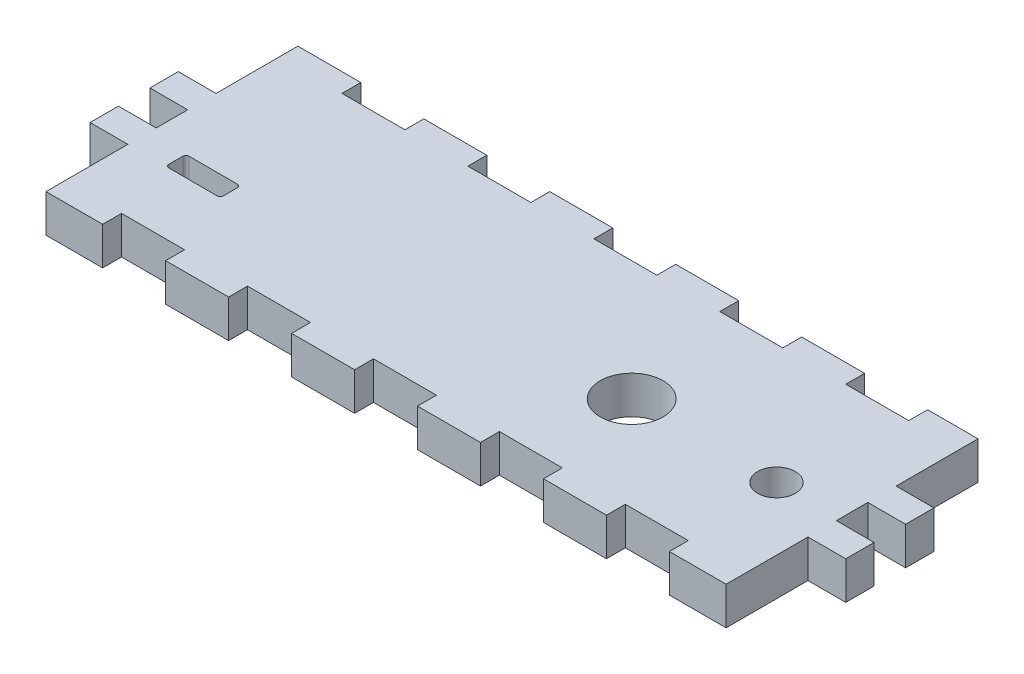
SolidWorks part; units mm, degrees
ref_plane "Спереди" through (0, 0, 0) normal (0, 0, 1) x (1, 0, 0)
ref_plane "Сверху" through (0, 0, 0) normal (0, 1, 0) x (1, 0, 0)
ref_plane "Справа" through (0, 0, 0) normal (1, 0, 0) x (0, 0, -1)
sketch "Эскиз1" plane through (0, 0, 0) normal (0, 1, 0) x (1, 0, 0)
  line L1 (0, 0) -> (112, 0)
  line L2 (0, 0) -> (0, -40)
  line L3 (0, -40) -> (112, -40)
  line L4 (112, 0) -> (112, -40)
  dimension "D1" = 40
  dimension "D2" = 112
extrude "Бобышка-Вытянуть1" add sketch "Эскиз1" along normal blind 6
sketch "Эскиз2" plane through (0, 6, 0) normal (0, 1, 0) x (1, 0, 0)
  line L1 (112, 0) -> (0, 0) construction
  line L2 (112, -40) -> (112, 0) construction
  circle A0 centre (102, -25) radius 3
  dimension "D1" = 6
  dimension "D2" = 22
  dimension "D3" = 10
extrude "Вырез-Вытянуть1" cut sketch "Эскиз2" against normal through all
sketch "Эскиз3" plane through (0, 6, 0) normal (0, 1, 0) x (1, 0, 0)
  line L0 (0, -40) -> (112, -40) construction
  line L1 (10.5, -26.78) -> (18.17, -26.78)
  line L2 (10, -27.28) -> (10, -29.5)
  line L3 (10.5, -30) -> (18.17, -30)
  line L4 (18.67, -27.28) -> (18.67, -29.5)
  line L5 (0, 0) -> (0, -40) construction
  arc A0 (10.5, -26.78) -> (10, -27.28) centre (10.5, -27.28) ccw
  arc A1 (10.5, -30) -> (10, -29.5) centre (10.5, -29.5) cw
  arc A2 (18.17, -30) -> (18.67, -29.5) centre (18.17, -29.5) ccw
  arc A3 (18.67, -27.28) -> (18.17, -26.78) centre (18.17, -27.28) ccw
  point P6 (10, -26.78)
  point P11 (18.67, -30)
  point P14 (18.67, -26.78)
  dimension "D3" = 0.5
  dimension "D4" = 0.5
  dimension "D5" = 0.5
  dimension "D6" = 0.5
  dimension "D1" = 8.67
  dimension "D2" = 3.22
  dimension "D7" = 10
  dimension "D8" = 10
extrude "Вырез-Вытянуть2" cut sketch "Эскиз3" against normal blind 10
sketch "Эскиз4" plane through (0, 6, 0) normal (0, 1, 0) x (1, 0, 0)
  line L0 (0, -40) -> (112, -40) construction
  circle A0 centre (79, -25) radius 4.9895
  circle A5 centre (102, -25) radius 3 construction
  dimension "D1" = 9.979
  dimension "D2" = 20
  dimension "D3" = 15
extrude "Вырез-Вытянуть3" cut sketch "Эскиз4" against normal through all
sketch "Эскиз6" plane through (112, 0, 0) normal (1, 0, 0) x (0, 0, -1)
  line L0 (-40, 6) -> (0, 6) construction
  line L1 (-30, 6) -> (-25.5, 6)
  line L2 (-30, 6) -> (-30, 0)
  line L3 (-30, 0) -> (-25.5, 0)
  line L4 (-25.5, 6) -> (-25.5, 0)
  line L5 (22, 0) -> (-22, 0) construction
  line L6 (-40, 6) -> (-40, 0) construction
  line L7 (-20.5, 6) -> (-16, 6)
  line L8 (-20.5, 6) -> (-20.5, 0)
  line L9 (-20.5, 0) -> (-16, 0)
  line L10 (-16, 6) -> (-16, 0)
  dimension "D1" = 4.5
  dimension "D2" = 4.5
  dimension "D3" = 5
  dimension "D4" = 10
extrude "Бобышка-Вытянуть3" add sketch "Эскиз6" along normal blind 6
sketch "Эскиз11" plane through (0, 0, 0) normal (-1, 0, 0) x (0, 0, 1)
  line L1 (0, 6) -> (40, 6)
  line L2 (0, 6) -> (0, 0)
  line L3 (0, 0) -> (40, 0)
  line L4 (40, 6) -> (40, 0)
extrude "Вырез-Вытянуть4" cut sketch "Эскиз11" against normal blind 4
sketch "Эскиз12" plane through (4, 0, 0) normal (-1, 0, 0) x (0, 0, 1)
  line L0 (40, 6) -> (0, 6) construction
  line L1 (16, 6) -> (20.5, 6)
  line L2 (16, 6) -> (16, 0)
  line L3 (16, 0) -> (20.5, 0)
  line L4 (20.5, 6) -> (20.5, 0)
  line L5 (0, 0) -> (40, 0) construction
  line L6 (22, 0) -> (-22, 0) construction
  line L7 (25.5, 6) -> (30, 6)
  line L8 (25.5, 6) -> (25.5, 0)
  line L9 (25.5, 0) -> (30, 0)
  line L10 (30, 6) -> (30, 0)
  line L11 (40, 0) -> (40, 6) construction
  dimension "D1" = 4.5
  dimension "D2" = 4.5
  dimension "D3" = 5
  dimension "D4" = 10
extrude "Бобышка-Вытянуть10" add sketch "Эскиз12" along normal blind 6
sketch "Эскиз13" plane through (0, 0, 40) normal (0, 0, 1) x (1, 0, 0)
  line L0 (22, 0) -> (-22, 0) construction
  line L1 (4, 6) -> (13, 6)
  line L2 (4, 6) -> (4, 0)
  line L3 (4, 0) -> (13, 0)
  line L4 (13, 6) -> (13, 0)
  line L5 (4, 6) -> (112, 6) construction
  line L6 (112, 6) -> (103, 6)
  line L7 (112, 6) -> (112, 0)
  line L8 (112, 0) -> (103, 0)
  line L9 (103, 6) -> (103, 0)
  line L10 (23, 6) -> (33, 6)
  line L11 (23, 6) -> (23, 0)
  line L12 (23, 0) -> (33, 0)
  line L13 (33, 6) -> (33, 0)
  line L15 (43, 6) -> (53, 6)
  line L16 (43, 6) -> (43, 0)
  line L17 (43, 0) -> (53, 0)
  line L18 (53, 6) -> (53, 0)
  line L19 (63, 6) -> (73, 6)
  line L20 (63, 6) -> (63, 0)
  line L21 (63, 0) -> (73, 0)
  line L22 (73, 6) -> (73, 0)
  line L23 (83, 6) -> (93, 6)
  line L24 (83, 6) -> (83, 0)
  line L25 (83, 0) -> (93, 0)
  line L26 (93, 6) -> (93, 0)
  dimension "D1" = 9
  dimension "D2" = 10
  dimension "D3" = 10
  dimension "D4" = 10
  dimension "D5" = 10
  dimension "D6" = 10
  dimension "D7" = 10
  dimension "D8" = 9
  dimension "D9" = 10
  dimension "D10" = 10
extrude "Бобышка-Вытянуть11" add sketch "Эскиз13" along normal blind 3
sketch "Эскиз14" plane through (0, 0, 0) normal (0, 0, -1) x (-1, 0, 0)
  line L1 (22, 0) -> (-22, 0) construction
  line L2 (-112, 6) -> (-4, 6)
  line L3 (-112, 6) -> (-112, 0)
  line L4 (-112, 0) -> (-4, 0)
  line L5 (-4, 6) -> (-4, 0)
  line L6 (-4, 6) -> (-4, 0) construction
extrude "Вырез-Вытянуть5" cut sketch "Эскиз14" against normal blind 2
sketch "Эскиз15" plane through (0, 0, 2) normal (0, 0, -1) x (-1, 0, 0)
  line L1 (-112, 6) -> (-4, 6)
  line L2 (-112, 6) -> (-112, 0)
  line L3 (-112, 0) -> (-4, 0)
  line L4 (-4, 6) -> (-4, 0)
extrude "Вырез-Вытянуть6" cut sketch "Эскиз15" against normal blind 2
sketch "Эскиз16" plane through (0, 0, 4) normal (0, 0, -1) x (-1, 0, 0)
  line L0 (-112, 0) -> (-4, 0) construction
  line L1 (-14, 0) -> (-24, 0)
  line L2 (-14, 0) -> (-14, 6)
  line L3 (-14, 6) -> (-24, 6)
  line L4 (-24, 0) -> (-24, 6)
  line L5 (-4, 6) -> (-112, 6) construction
  line L6 (-4, 0) -> (-4, 6) construction
  line L7 (-34, 0) -> (-34, 6)
  line L8 (-34, 0) -> (-44, 0)
  line L9 (-44, 0) -> (-44, 6)
  line L10 (-34, 6) -> (-44, 6)
  line L11 (-54, 0) -> (-54, 6)
  line L12 (-54, 0) -> (-64, 0)
  line L13 (-64, 0) -> (-64, 6)
  line L14 (-54, 6) -> (-64, 6)
  line L15 (-74, 0) -> (-74, 6)
  line L16 (-74, 0) -> (-84, 0)
  line L17 (-84, 0) -> (-84, 6)
  line L18 (-74, 6) -> (-84, 6)
  line L19 (-94, 0) -> (-94, 6)
  line L20 (-94, 0) -> (-104, 0)
  line L21 (-104, 0) -> (-104, 6)
  line L22 (-94, 6) -> (-104, 6)
  dimension "D1" = 10
  dimension "D2" = 10
  dimension "D3" = 5
extrude "Вырез-Вытянуть7" cut sketch "Эскиз16" against normal blind 3
sketch "Эскиз17" plane through (0, 0, 4) normal (0, 0, -1) x (-1, 0, 0)
  line L1 (-14, 6) -> (-4, 6)
  line L2 (-14, 6) -> (-14, 0)
  line L3 (-14, 0) -> (-4, 0)
  line L4 (-4, 6) -> (-4, 0)
  line L5 (-34, 6) -> (-24, 6)
  line L6 (-34, 6) -> (-34, 0)
  line L7 (-34, 0) -> (-24, 0)
  line L8 (-24, 6) -> (-24, 0)
  line L9 (-54, 6) -> (-44, 6)
  line L10 (-54, 6) -> (-54, 0)
  line L11 (-54, 0) -> (-44, 0)
  line L12 (-44, 6) -> (-44, 0)
  line L13 (-74, 6) -> (-64, 6)
  line L14 (-74, 6) -> (-74, 0)
  line L15 (-74, 0) -> (-64, 0)
  line L16 (-64, 6) -> (-64, 0)
  line L17 (-94, 6) -> (-84, 6)
  line L18 (-94, 6) -> (-94, 0)
  line L19 (-94, 0) -> (-84, 0)
  line L20 (-84, 6) -> (-84, 0)
  line L21 (-112, 6) -> (-104, 6)
  line L22 (-112, 6) -> (-112, 0)
  line L23 (-112, 0) -> (-104, 0)
  line L24 (-104, 6) -> (-104, 0)
extrude "Бобышка-Вытянуть12" add sketch "Эскиз17" along normal blind 1
sketch "Эскиз18" plane through (0, 0, 7) normal (0, 0, -1) x (-1, 0, 0)
  line L1 (-14, 6) -> (-24, 6)
  line L2 (-14, 6) -> (-14, 0)
  line L3 (-14, 0) -> (-24, 0)
  line L4 (-24, 6) -> (-24, 0)
  line L5 (-44, 6) -> (-34, 6)
  line L6 (-44, 6) -> (-44, 0)
  line L7 (-44, 0) -> (-34, 0)
  line L8 (-34, 6) -> (-34, 0)
  line L9 (-54, 6) -> (-64, 6)
  line L10 (-54, 6) -> (-54, 0)
  line L11 (-54, 0) -> (-64, 0)
  line L12 (-64, 6) -> (-64, 0)
  line L13 (-84, 6) -> (-74, 6)
  line L14 (-84, 6) -> (-84, 0)
  line L15 (-84, 0) -> (-74, 0)
  line L16 (-74, 6) -> (-74, 0)
  line L17 (-94, 6) -> (-104, 6)
  line L18 (-94, 6) -> (-94, 0)
  line L19 (-94, 0) -> (-104, 0)
  line L20 (-104, 6) -> (-104, 0)
extrude "Бобышка-Вытянуть13" add sketch "Эскиз18" along normal blind 1
